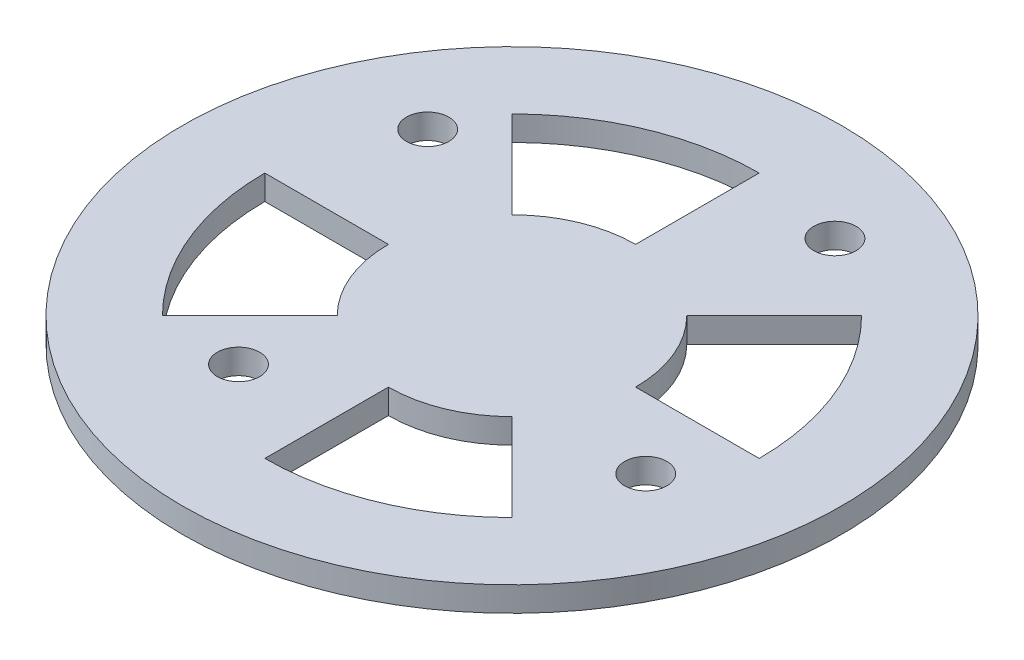
SolidWorks part; units mm, degrees
ref_plane "Front Plane" through (0, 0, 0) normal (0, 0, 1) x (1, 0, 0)
ref_plane "Top Plane" through (0, 0, 0) normal (0, 1, 0) x (1, 0, 0)
ref_plane "Right Plane" through (0, 0, 0) normal (1, 0, 0) x (0, 0, -1)
sketch "Sketch1" plane through (0, 0, 0) normal (0, 1, 0) x (1, 0, 0)
  circle A0 centre (0, 0) radius 50.8
  dimension "D1" = 101.6
extrude "Boss-Extrude1" add sketch "Sketch1" along normal blind 19.05
sketch "Sketch4" plane through (0, 19.05, 0) normal (0, 1, 0) x (1, 0, 0)
  line L0 (-3.5195, 6.096) -> (3.5195, 6.096)
  line L1 (3.5195, 6.096) -> (7.0391, 0)
  line L2 (7.0391, 0) -> (3.5195, -6.096)
  line L3 (3.5195, -6.096) -> (-3.5195, -6.096)
  line L4 (-3.5195, -6.096) -> (-7.0391, 0)
  line L5 (-7.0391, 0) -> (-3.5195, 6.096)
  point P7 (0, 6.096)
  dimension "D1" = 120
  dimension "D2" = 12.192
extrude "Cut-Extrude2" cut sketch "Sketch4" against normal blind 15.24 contours L5 L0 L1 L2 L3 L4
sketch "Sketch5" plane through (0, 3.81, 0) normal (0, 1, 0) x (1, 0, 0)
  circle A0 centre (0, 0) radius 4.064
  dimension "D1" = 8.128
extrude "Cut-Extrude3" cut sketch "Sketch5" against normal through all contours A0
sketch "Sketch6" plane through (0, 19.05, 0) normal (0, 1, 0) x (1, 0, 0)
  line L0 (0, 0) -> (0, 38.1)
  line L1 (0, 0) -> (26.9408, 26.9408)
  line L2 (0, 0) -> (38.1, 0)
  line L3 (0, 0) -> (26.9408, -26.9408)
  line L4 (0, 0) -> (0, -38.1)
  line L5 (0, 0) -> (-26.9408, -26.9408)
  line L6 (0, 0) -> (-38.1, 0)
  line L7 (0, 0) -> (-26.9408, 26.9408)
  circle A0 centre (0, 0) radius 38.1
  circle A1 centre (0, 0) radius 19.05
  point P15 (0, 0)
  dimension "D1" = 38.1
  dimension "D2" = 76.2
  dimension "D3" = 45
  dimension "D4" = 4
extrude "Cut-Extrude4" cut sketch "Sketch6" against normal through all contours A1 L0 A0 L7 | A1 L2 A0 L1 | A1 L4 A0 L3 | A1 L6 A0 L5
sketch "Sketch7" plane through (0, 19.05, 0) normal (0, 1, 0) x (1, 0, 0)
  line L27 (16.3134, -2.54) -> (40.5605, -2.54)
  line L28 (26.8846, 30.4767) -> (9.7393, 13.3314)
  line L29 (2.54, 16.3134) -> (2.54, 40.5605)
  line L30 (-30.4767, 26.8846) -> (-13.3314, 9.7393)
  line L31 (2.54, 16.3134) -> (2.54, 40.5605)
  line L32 (-30.4767, 26.8846) -> (-13.3314, 9.7393)
  line L33 (-2.54, -16.3134) -> (-2.54, -40.5605)
  line L34 (30.4767, -26.8846) -> (13.3314, -9.7393)
  line L35 (-16.3134, 2.54) -> (-40.5605, 2.54)
  line L36 (-26.8846, -30.4767) -> (-9.7393, -13.3314)
  line L64 (9.972, 0) -> (4.986, 8.636)
  line L65 (4.986, -8.636) -> (9.972, 0)
  line L66 (-4.986, -8.636) -> (4.986, -8.636)
  line L67 (-9.972, 0) -> (-4.986, -8.636)
  line L68 (-4.986, 8.636) -> (-9.972, 0)
  line L69 (4.986, 8.636) -> (-4.986, 8.636)
  line L70 (9.972, 0) -> (4.986, 8.636)
  line L71 (4.986, -8.636) -> (9.972, 0)
  line L72 (-4.986, -8.636) -> (4.986, -8.636)
  line L73 (-9.972, 0) -> (-4.986, -8.636)
  line L74 (-4.986, 8.636) -> (-9.972, 0)
  line L75 (4.986, 8.636) -> (-4.986, 8.636)
  arc A28 (40.5605, -2.54) -> (26.8846, 30.4767) centre (0, 0) ccw
  arc A29 (16.3134, -2.54) -> (9.7393, 13.3314) centre (0, 0) ccw
  arc A30 (2.54, 16.3134) -> (-13.3314, 9.7393) centre (0, 0) ccw
  arc A31 (2.54, 40.5605) -> (-30.4767, 26.8846) centre (0, 0) ccw
  arc A32 (2.54, 16.3134) -> (-13.3314, 9.7393) centre (0, 0) ccw
  arc A33 (2.54, 40.5605) -> (-30.4767, 26.8846) centre (0, 0) ccw
  arc A34 (-2.54, -40.5605) -> (30.4767, -26.8846) centre (0, 0) ccw
  arc A35 (-2.54, -16.3134) -> (13.3314, -9.7393) centre (0, 0) ccw
  arc A36 (-40.5605, 2.54) -> (-26.8846, -30.4767) centre (0, 0) ccw
  arc A37 (-16.3134, 2.54) -> (-9.7393, -13.3314) centre (0, 0) ccw
  circle A40 centre (0, 0) radius 48.26
  circle A41 centre (0, 0) radius 50.8 construction
  point P15 (0, 0)
  dimension "D4" = 2.54
  dimension "D1" = 2.54
  dimension "D3" = 2.54
  dimension "D2" = 4
extrude "Cut-Extrude5" cut sketch "Sketch7" against normal up to surface (15.24 mm away) contours A40 L35 A37 L36 A36 L27 A29 L28 A28 L75 L70 L71 L72 L73 L74 A33 L31 A32 L32 L33 A35 L34 A34 up to face at (0, 3.81, 4.064)
sketch "Sketch8" plane through (0, 3.81, 0) normal (0, 1, 0) x (1, 0, 0)
  line L1 (14.5802, 35.1998) -> (0, 0) construction
  line L2 (2.54, 16.3134) -> (2.54, 40.5605) construction
  circle A0 centre (14.5802, 35.1998) radius 3.2639
  circle A1 centre (31.3898, -10.7702) radius 3.2639
  circle A2 centre (-14.5802, -27.5798) radius 3.2639
  circle A3 centre (-31.3898, 18.3902) radius 3.2639
  point P15 (0, 3.81)
  dimension "D3" = 6.5278
  dimension "D1" = 38.1
  dimension "D2" = 22.5
  dimension "D4" = 4
extrude "Cut-Extrude6" cut sketch "Sketch8" against normal through all
sketch "Sketch9" plane through (0, 19.05, 0) normal (0, 1, 0) x (1, 0, 0)
  circle A0 centre (0, 0) radius 50.8
  circle A1 centre (0, 0) radius 50.8 construction
extrude "Cut-Extrude7" cut sketch "Sketch9" against normal up to surface (15.24 mm away) up to face at (14.5802, 3.81, -31.9359)
sketch "Sketch10" plane through (0, 3.81, 0) normal (0, 1, 0) x (1, 0, 0)
  circle A0 centre (0, 0) radius 6.216
extrude "Boss-Extrude2" add sketch "Sketch10" against normal up to surface (3.81 mm away) up to face at (14.5802, 0, -31.9359)
